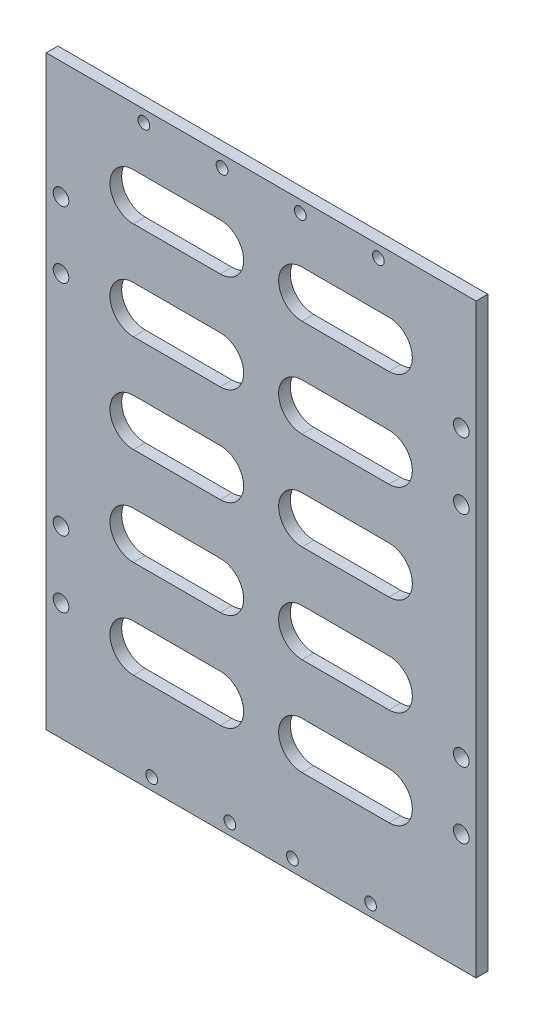
SolidWorks part; units mm, degrees
ref_plane "前视基准面" through (0, 0, 0) normal (0, 0, 1) x (1, 0, 0)
ref_plane "上视基准面" through (0, 0, 0) normal (0, 1, 0) x (1, 0, 0)
ref_plane "右视基准面" through (0, 0, 0) normal (1, 0, 0) x (0, 0, -1)
other "Configuration Table"
sketch "草图1" plane through (0, 0, 0) normal (0, 0, 1) x (1, 0, 0)
  line L1 (0, 0) -> (110, 0)
  line L2 (0, 0) -> (0, 150)
  line L3 (0, 150) -> (110, 150)
  line L4 (110, 0) -> (110, 150)
  dimension "D1" = 110
  dimension "D2" = 150
extrude "凸台-拉伸1" add sketch "草图1" along normal blind 3
sketch "草图2" plane through (0, 0, 3) normal (0, 0, 1) x (1, 0, 0)
  line L0 (55, 150) -> (55, 0) construction
  line L1 (110, 150) -> (0, 150) construction
  line L2 (0, 0) -> (110, 0) construction
  circle A0 centre (45, 147) radius 1.5
  circle A1 centre (25, 147) radius 1.5
  circle A2 centre (85, 147) radius 1.5
  circle A3 centre (65, 147) radius 1.5
  dimension "D1" = 3
  dimension "D4" = 3
  dimension "D2" = 10
  dimension "D3" = 3
  dimension "D5" = 20
  dimension "D6" = 3
extrude "切除-拉伸1" cut sketch "草图2" against normal blind 3
sketch "草图3" plane through (0, 0, 3) normal (0, 0, 1) x (1, 0, 0)
  line L0 (55, 150) -> (55, 0) construction
  line L1 (110, 150) -> (0, 150) construction
  line L2 (0, 0) -> (110, 0) construction
  line L3 (0, 75) -> (110, 75) construction
  line L4 (0, 150) -> (0, 0) construction
  line L5 (110, 0) -> (110, 150) construction
  circle A0 centre (3.8, 47) radius 2
  circle A1 centre (3.8, 30) radius 2
  circle A2 centre (106.2, 30) radius 2
  circle A3 centre (106.2, 47) radius 2
  circle A4 centre (106.2, 103) radius 2
  circle A5 centre (106.2, 120) radius 2
  circle A6 centre (3.8, 120) radius 2
  circle A7 centre (3.8, 103) radius 2
  dimension "D1" = 4
  dimension "D2" = 4
  dimension "D3" = 17
  dimension "D4" = 3.8
  dimension "D5" = 30
  dimension "D6" = 3.8
extrude "切除-拉伸2" cut sketch "草图3" against normal through all
sketch "草图4" plane through (0, 0, 3) normal (0, 0, 1) x (1, 0, 0)
  line L0 (55, 150) -> (55, 0) construction
  line L1 (110, 150) -> (0, 150) construction
  line L2 (0, 0) -> (110, 0) construction
  circle A0 centre (63, 3) radius 1.5
  circle A1 centre (83, 3) radius 1.5
  circle A2 centre (27, 3) radius 1.5
  circle A3 centre (47, 3) radius 1.5
  dimension "D1" = 3
  dimension "D2" = 3
extrude "切除-拉伸3" cut sketch "草图4" against normal through all
sketch "草图5" plane through (0, 0, 3) normal (0, 0, 1) x (1, 0, 0)
  line L0 (55, 150) -> (55, 0) construction
  line L1 (110, 150) -> (0, 150) construction
  line L2 (0, 0) -> (110, 0) construction
  line L3 (22.3194, 129.2528) -> (44.5254, 129.2528) construction
  line L4 (22.3194, 135.2528) -> (44.5254, 135.2528)
  line L5 (22.3194, 123.2528) -> (44.5254, 123.2528)
  line L6 (22.3194, 104.2528) -> (44.5254, 104.2528) construction
  line L7 (22.3194, 110.2528) -> (44.5254, 110.2528)
  line L8 (22.3194, 98.2528) -> (44.5254, 98.2528)
  line L9 (22.3194, 79.2528) -> (44.5254, 79.2528) construction
  line L10 (22.3194, 85.2528) -> (44.5254, 85.2528)
  line L11 (22.3194, 73.2528) -> (44.5254, 73.2528)
  line L12 (22.3194, 54.2528) -> (44.5254, 54.2528) construction
  line L13 (22.3194, 60.2528) -> (44.5254, 60.2528)
  line L14 (22.3194, 48.2528) -> (44.5254, 48.2528)
  line L15 (22.3194, 29.2528) -> (44.5254, 29.2528) construction
  line L16 (22.3194, 35.2528) -> (44.5254, 35.2528)
  line L17 (22.3194, 23.2528) -> (44.5254, 23.2528)
  line L18 (87.6806, 29.2528) -> (65.4746, 29.2528) construction
  line L19 (87.6806, 35.2528) -> (65.4746, 35.2528)
  line L20 (87.6806, 23.2528) -> (65.4746, 23.2528)
  line L21 (87.6806, 54.2528) -> (65.4746, 54.2528) construction
  line L22 (87.6806, 60.2528) -> (65.4746, 60.2528)
  line L23 (87.6806, 48.2528) -> (65.4746, 48.2528)
  line L24 (87.6806, 79.2528) -> (65.4746, 79.2528) construction
  line L25 (87.6806, 85.2528) -> (65.4746, 85.2528)
  line L26 (87.6806, 73.2528) -> (65.4746, 73.2528)
  line L27 (87.6806, 104.2528) -> (65.4746, 104.2528) construction
  line L28 (87.6806, 110.2528) -> (65.4746, 110.2528)
  line L29 (87.6806, 98.2528) -> (65.4746, 98.2528)
  line L30 (87.6806, 129.2528) -> (65.4746, 129.2528) construction
  line L31 (87.6806, 135.2528) -> (65.4746, 135.2528)
  line L32 (87.6806, 123.2528) -> (65.4746, 123.2528)
  arc A0 (22.3194, 135.2528) -> (22.3194, 123.2528) centre (22.3194, 129.2528) ccw
  arc A1 (44.5254, 123.2528) -> (44.5254, 135.2528) centre (44.5254, 129.2528) ccw
  arc A2 (22.3194, 110.2528) -> (22.3194, 98.2528) centre (22.3194, 104.2528) ccw
  arc A3 (44.5254, 98.2528) -> (44.5254, 110.2528) centre (44.5254, 104.2528) ccw
  arc A4 (22.3194, 85.2528) -> (22.3194, 73.2528) centre (22.3194, 79.2528) ccw
  arc A5 (44.5254, 73.2528) -> (44.5254, 85.2528) centre (44.5254, 79.2528) ccw
  arc A6 (22.3194, 60.2528) -> (22.3194, 48.2528) centre (22.3194, 54.2528) ccw
  arc A7 (44.5254, 48.2528) -> (44.5254, 60.2528) centre (44.5254, 54.2528) ccw
  arc A8 (22.3194, 35.2528) -> (22.3194, 23.2528) centre (22.3194, 29.2528) ccw
  arc A9 (44.5254, 23.2528) -> (44.5254, 35.2528) centre (44.5254, 29.2528) ccw
  arc A10 (87.6806, 35.2528) -> (87.6806, 23.2528) centre (87.6806, 29.2528) cw
  arc A11 (65.4746, 23.2528) -> (65.4746, 35.2528) centre (65.4746, 29.2528) cw
  arc A12 (87.6806, 60.2528) -> (87.6806, 48.2528) centre (87.6806, 54.2528) cw
  arc A13 (65.4746, 48.2528) -> (65.4746, 60.2528) centre (65.4746, 54.2528) cw
  arc A14 (87.6806, 85.2528) -> (87.6806, 73.2528) centre (87.6806, 79.2528) cw
  arc A15 (65.4746, 73.2528) -> (65.4746, 85.2528) centre (65.4746, 79.2528) cw
  arc A16 (87.6806, 110.2528) -> (87.6806, 98.2528) centre (87.6806, 104.2528) cw
  arc A17 (65.4746, 98.2528) -> (65.4746, 110.2528) centre (65.4746, 104.2528) cw
  arc A18 (87.6806, 135.2528) -> (87.6806, 123.2528) centre (87.6806, 129.2528) cw
  arc A19 (65.4746, 123.2528) -> (65.4746, 135.2528) centre (65.4746, 129.2528) cw
  point P8 (33.4224, 129.2528)
  point P16 (33.4224, 104.2528)
  point P23 (33.4224, 79.2528)
  point P30 (33.4224, 54.2528)
  point P37 (33.4224, 29.2528)
  point P43 (76.5776, 29.2528)
  point P50 (76.5776, 54.2528)
  point P57 (76.5776, 79.2528)
  point P64 (76.5776, 104.2528)
  point P71 (76.5776, 129.2528)
  dimension "D1" = 5
  dimension "D2" = 12
extrude "切除-拉伸4" cut sketch "草图5" against normal blind 10
